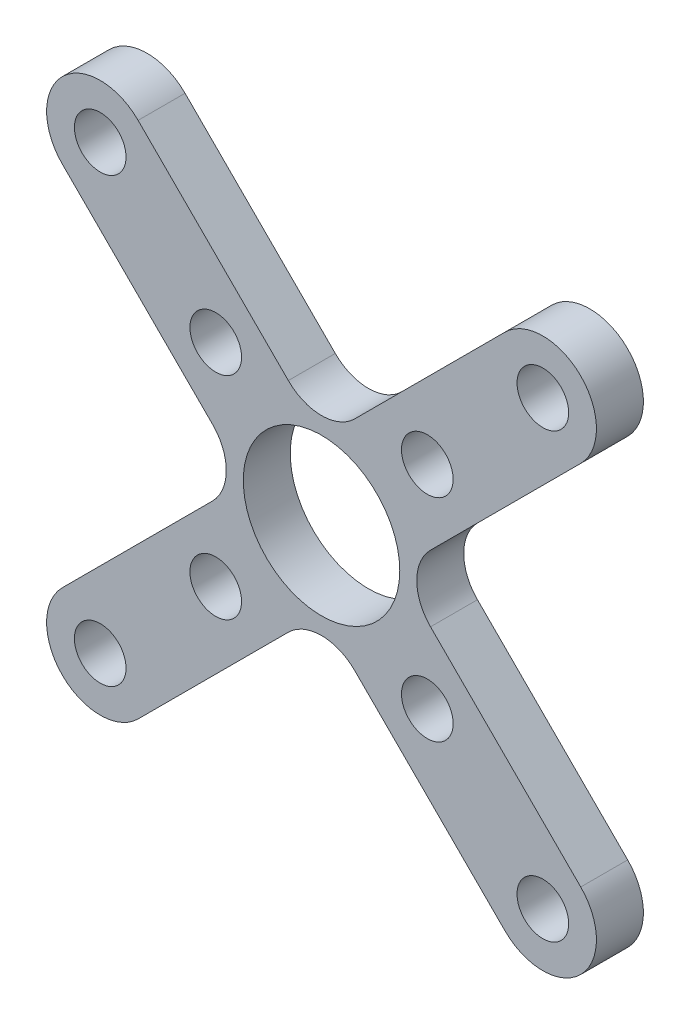
SolidWorks part; units mm, degrees
ref_plane "Front Plane" through (0, 0, 0) normal (0, 0, 1) x (1, 0, 0)
ref_plane "Top Plane" through (0, 0, 0) normal (0, 1, 0) x (1, 0, 0)
ref_plane "Right Plane" through (0, 0, 0) normal (1, 0, 0) x (0, 0, -1)
sketch "Sketch1" plane through (0, 0, 0) normal (0, 0, 1) x (1, 0, 0)
  line L0 (14.1421, 14.1421) -> (-14.1421, -14.1421) construction
  line L1 (16.5634, 11.7208) -> (6.9639, 2.1213)
  line L2 (11.7208, 16.5634) -> (2.1213, 6.9639)
  line L3 (-35.8279, 0) -> (35.8279, 0) construction
  line L4 (0, 22.9899) -> (0, -22.9899) construction
  line L5 (-14.1421, 14.1421) -> (14.1421, -14.1421) construction
  line L6 (-16.5634, 11.7208) -> (-6.9639, 2.1213)
  line L7 (-11.7208, 16.5634) -> (-2.1213, 6.9639)
  line L8 (-6.9639, -2.1213) -> (-16.5634, -11.7208)
  line L9 (2.1213, -6.9639) -> (11.7208, -16.5634)
  line L10 (-2.1213, -6.9639) -> (-11.7208, -16.5634)
  line L11 (6.9639, -2.1213) -> (16.5634, -11.7208)
  arc A0 (16.5634, 11.7208) -> (11.7208, 16.5634) centre (14.1421, 14.1421) ccw
  arc A1 (-16.5634, -11.7208) -> (-11.7208, -16.5634) centre (-14.1421, -14.1421) ccw
  arc A2 (-16.5634, 11.7208) -> (-11.7208, 16.5634) centre (-14.1421, 14.1421) cw
  arc A3 (16.5634, -11.7208) -> (11.7208, -16.5634) centre (14.1421, -14.1421) cw
  arc A4 (-6.9639, 2.1213) -> (-6.9639, -2.1213) centre (-9.0852, 0) cw
  arc A5 (-2.1213, -6.9639) -> (2.1213, -6.9639) centre (0, -9.0852) cw
  arc A6 (6.9639, -2.1213) -> (6.9639, 2.1213) centre (9.0852, 0) cw
  arc A7 (2.1213, 6.9639) -> (-2.1213, 6.9639) centre (0, 9.0852) cw
  circle A8 centre (-14.1421, 14.1421) radius 1.65
  circle A9 centre (14.1421, 14.1421) radius 1.65
  circle A10 centre (-14.1421, -14.1421) radius 1.65
  circle A11 centre (14.1421, -14.1421) radius 1.65
  circle A12 centre (0, 0) radius 5
  circle A13 centre (-6.7599, 6.7599) radius 1.65
  circle A14 centre (6.7599, 6.7599) radius 1.65
  circle A15 centre (6.7599, -6.7599) radius 1.65
  circle A16 centre (-6.7599, -6.7599) radius 1.65
  point P2 (0, 0)
  point P12 (0, 0)
  point P14 (0, 0)
  point P16 (0, 0)
  point P27 (-4.8426, 0)
  point P30 (0, -4.8426)
  point P33 (4.8426, 0)
  point P36 (0, 4.8426)
  dimension "D3" = 3.3
  dimension "D4" = 3
  dimension "D5" = 3.3
  dimension "D1" = 40
  dimension "D2" = 45
extrude "Boss-Extrude1" add sketch "Sketch1" along normal blind 3 contours L8 A1 L10 A5 L9 A3 L11 A6 L1 A0 L2 A7 L7 A2 L6 A4 | A8 | A9 | A11 | A10 | A12 | A13 | A14 | A15 | A16
